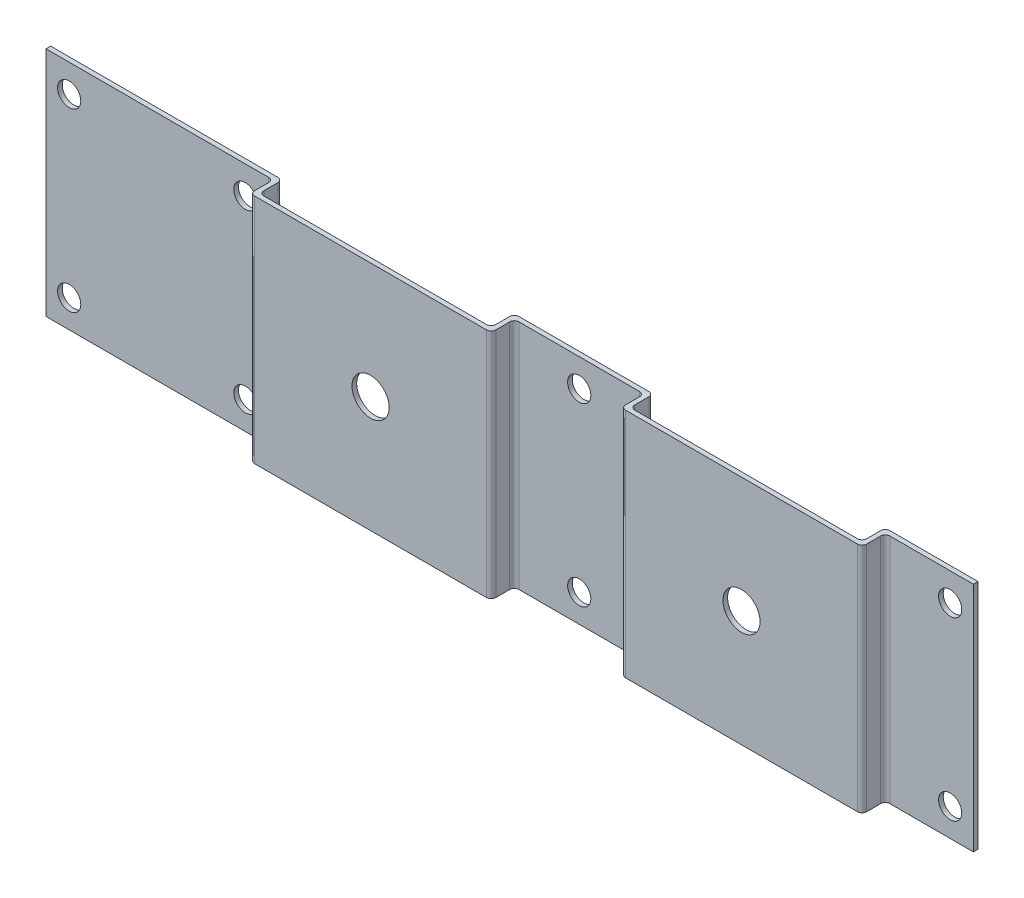
SolidWorks part; units mm, degrees
ref_plane "Front Plane" through (0, 0, 0) normal (0, 0, 1) x (1, 0, 0)
ref_plane "Top Plane" through (0, 0, 0) normal (0, 1, 0) x (1, 0, 0)
ref_plane "Right Plane" through (0, 0, 0) normal (1, 0, 0) x (0, 0, -1)
sketch "Sketch1" plane through (0, 0, 0) normal (0, 0, 1) x (1, 0, 0)
  line L1 (-25, -25) -> (25, -25)
  line L2 (-25, -25) -> (-25, 25)
  line L3 (-25, 25) -> (25, 25)
  line L4 (25, -25) -> (25, 25)
  line L5 (-25, -25) -> (25, 25) construction
  line L6 (-25, 25) -> (25, -25) construction
  point P0 (0, 0)
  dimension "D1" = 50
  dimension "D2" = 50
extrude "Boss-Extrude1" add sketch "Sketch1" along normal blind 1
sketch "Sketch2" plane through (0, 0, 0) normal (0, 0, 1) x (1, 0, 0)
  line L0 (25, -25) -> (25, 25) construction
  line L1 (25, -25) -> (75, -25)
  line L2 (25, -25) -> (25, 25)
  line L3 (25, 25) -> (75, 25)
  line L4 (75, -25) -> (75, 25)
  line L5 (25, -25) -> (75, 25) construction
  line L6 (25, 25) -> (75, -25) construction
  point P0 (50, 0)
  dimension "D1" = 50
  dimension "D2" = 50
extrude "Boss-Extrude2" add sketch "Sketch2" along normal blind 1 from offset 5 separate body
sketch "Sketch3" plane through (0, 0, 0) normal (0, 0, 1) x (1, 0, 0)
  line L0 (75, -25) -> (75, 25) construction
  line L1 (75, -25) -> (105, -25)
  line L2 (75, -25) -> (75, 25)
  line L3 (75, 25) -> (105, 25)
  line L4 (105, -25) -> (105, 25)
  line L5 (75, -25) -> (105, 25) construction
  line L6 (75, 25) -> (105, -25) construction
  point P0 (90, 0)
  dimension "D1" = 30
  dimension "D2" = 50
extrude "Boss-Extrude3" add sketch "Sketch3" along normal blind 1 separate body
sketch "Sketch4" plane through (0, 0, 0) normal (0, 0, 1) x (1, 0, 0)
  line L0 (105, -25) -> (105, 25) construction
  line L1 (105, -25) -> (155, -25)
  line L2 (105, -25) -> (105, 25)
  line L3 (105, 25) -> (155, 25)
  line L4 (155, -25) -> (155, 25)
  line L5 (105, -25) -> (155, 25) construction
  line L6 (105, 25) -> (155, -25) construction
  point P0 (130, 0)
  dimension "D1" = 50
  dimension "D2" = 50
extrude "Boss-Extrude4" add sketch "Sketch4" along normal blind 1 from offset 5 separate body
sketch "Sketch5" plane through (0, 0, 0) normal (0, 0, 1) x (1, 0, 0)
  line L0 (155, -25) -> (155, 25) construction
  line L1 (155, -25) -> (175, -25)
  line L2 (155, -25) -> (155, 25)
  line L3 (155, 25) -> (175, 25)
  line L4 (175, -25) -> (175, 25)
  line L5 (155, -25) -> (175, 25) construction
  line L6 (155, 25) -> (175, -25) construction
  point P0 (165, 0)
  dimension "D1" = 20
  dimension "D2" = 50
extrude "Boss-Extrude5" add sketch "Sketch5" along normal blind 1 separate body
sketch "Sketch6" plane through (25, 0, 0) normal (-1, 0, 0) x (0, 0, 1)
  line L0 (6, 25) -> (6, -25) construction
  line L1 (0, -25) -> (6, -25)
  line L2 (0, -25) -> (0, 25)
  line L3 (0, 25) -> (6, 25)
  line L4 (6, -25) -> (6, 25)
  line L5 (0, -25) -> (6, 25) construction
  line L6 (0, 25) -> (6, -25) construction
  line L7 (0, 25) -> (0, -25) construction
  line L8 (6, 25) -> (5, 25) construction
  line L9 (1, 25) -> (0, 25) construction
  point P0 (3, 0)
extrude "Boss-Extrude6" add sketch "Sketch6" along normal blind 1
sketch "Sketch7" plane through (75, 0, 0) normal (1, 0, 0) x (0, 0, -1)
  line L0 (-6, 25) -> (-5, 25) construction
  line L1 (-6, -25) -> (0, -25)
  line L2 (-6, -25) -> (-6, 25)
  line L3 (-6, 25) -> (0, 25)
  line L4 (0, -25) -> (0, 25)
  line L5 (-6, -25) -> (0, 25) construction
  line L6 (-6, 25) -> (0, -25) construction
  line L7 (-6, -25) -> (-6, 25) construction
  line L8 (0, 25) -> (0, -25) construction
  point P0 (-3, 0)
extrude "Boss-Extrude7" add sketch "Sketch7" along normal blind 1
sketch "Sketch8" plane through (105, 0, 0) normal (-1, 0, 0) x (0, 0, 1)
  line L0 (6, 25) -> (5, 25) construction
  line L1 (0, -25) -> (6, -25)
  line L2 (0, -25) -> (0, 25)
  line L3 (0, 25) -> (6, 25)
  line L4 (6, -25) -> (6, 25)
  line L5 (0, -25) -> (6, 25) construction
  line L6 (0, 25) -> (6, -25) construction
  line L7 (6, 25) -> (6, -25) construction
  line L8 (0, -25) -> (0, 25) construction
  point P0 (3, 0)
extrude "Boss-Extrude8" add sketch "Sketch8" along normal blind 1
sketch "Sketch9" plane through (155, 0, 0) normal (1, 0, 0) x (0, 0, -1)
  line L0 (-6, 25) -> (-5, 25) construction
  line L1 (-6, -25) -> (0, -25)
  line L2 (-6, -25) -> (-6, 25)
  line L3 (-6, 25) -> (0, 25)
  line L4 (0, -25) -> (0, 25)
  line L5 (-6, -25) -> (0, 25) construction
  line L6 (-6, 25) -> (0, -25) construction
  line L7 (-6, -25) -> (-6, 25) construction
  line L8 (0, 25) -> (0, -25) construction
  point P0 (-3, 0)
extrude "Boss-Extrude9" add sketch "Sketch9" along normal blind 1
fillet "Fillet1" radius 1 1 edges at (24, 0, 1)
fillet "Fillet2" radius 1 1 edges at (24, 0, 6)
fillet "Fillet3" radius 1 1 edges at (76, 0, 6)
fillet "Fillet4" radius 1 1 edges at (76, 0, 1)
fillet "Fillet5" radius 1 1 edges at (104, 0, 6)
fillet "Fillet6" radius 1 1 edges at (104, 0, 1)
fillet "Fillet7" radius 1 1 edges at (156, 0, 6)
fillet "Fillet8" radius 1 1 edges at (156, 0, 1)
fillet "Fillet9" radius 1 1 edges at (155, 0, 0)
fillet "Fillet10" radius 1 1 edges at (155, 0, 5)
fillet "Fillet11" radius 1 1 edges at (105, 0, 5)
fillet "Fillet12" radius 1 1 edges at (105, 0, 0)
fillet "Fillet13" radius 1 1 edges at (25, 0, 5)
fillet "Fillet14" radius 1 1 edges at (25, 0, 0)
fillet "Fillet15" radius 1 1 edges at (75, 0, 5)
fillet "Fillet16" radius 1 1 edges at (75, 0, 0)
sketch "Sketch10" plane through (0, 0, 1) normal (0, 0, 1) x (1, 0, 0)
  line L0 (-25, 25) -> (-25, -25) construction
  line L1 (23, -25) -> (23, 25) construction
  line L2 (23, 25) -> (-25, 25) construction
  line L3 (-25, -25) -> (23, -25) construction
  circle A0 centre (-20, 19) radius 2.5
  circle A1 centre (-20, -19) radius 2.5
  circle A2 centre (18, -19) radius 2.5
  circle A3 centre (18, 19) radius 2.5
  dimension "D1" = 5
  dimension "D2" = 5
  dimension "D3" = 5
  dimension "D4" = 6
  dimension "D5" = 6
extrude "Cut-Extrude1" cut sketch "Sketch10" against normal blind 1
sketch "Sketch11" plane through (0, 0, 0) normal (0, 0, 1) x (1, 0, 0)
  line L0 (103, 25) -> (77, 25) construction
  line L1 (25, 25) -> (25, -25) construction
  line L2 (77, -25) -> (103, -25) construction
  line L3 (105, 25) -> (105, -25) construction
  line L4 (175, -25) -> (175, 25) construction
  circle A0 centre (50, 0) radius 4
  circle A1 centre (130, 0) radius 4
  circle A2 centre (90, 19) radius 2.5
  circle A3 centre (90, -19) radius 2.5
  circle A4 centre (170, 19) radius 2.5
  circle A5 centre (170, -19) radius 2.5
  point P16 (25, 0)
  dimension "D1" = 8
  dimension "D2" = 8
  dimension "D3" = 5
  dimension "D5" = 25
  dimension "D4" = 25
  dimension "D6" = 40
  dimension "D7" = 40
  dimension "D8" = 6
  dimension "D9" = 6
  dimension "D10" = 5
extrude "Cut-Extrude7" cut sketch "Sketch11" against normal mid plane 101
